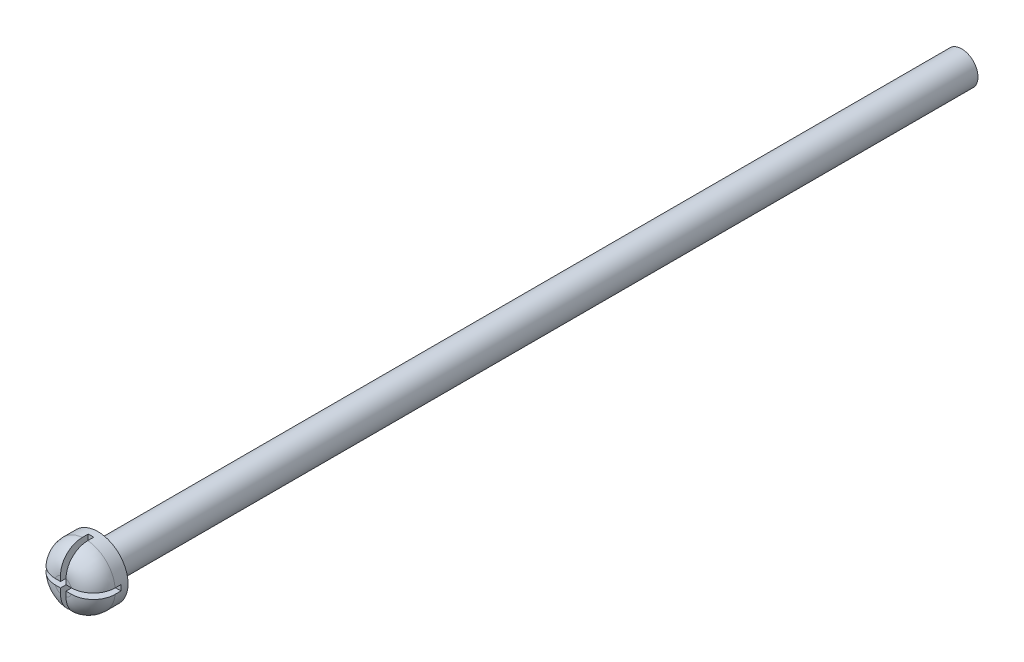
SolidWorks part; units mm, degrees
material "1060 Alloy"
ref_plane "Front Plane" through (0, 0, 0) normal (0, 0, 1) x (1, 0, 0)
ref_plane "Top Plane" through (0, 0, 0) normal (0, 1, 0) x (1, 0, 0)
ref_plane "Right Plane" through (0, 0, 0) normal (1, 0, 0) x (0, 0, -1)
sketch "Sketch1" plane through (0, 0, 0) normal (0, 0, 1) x (1, 0, 0)
  circle A0 centre (0, 0) radius 1.5
  dimension "D1" = 3
extrude "Boss-Extrude1" add sketch "Sketch1" along normal blind 82.55
sketch "Sketch3" plane through (0, 0, 82.55) normal (0, 0, 1) x (1, 0, 0)
  circle A0 centre (0, 0) radius 2.775
  dimension "D1" = 5.55
extrude "Boss-Extrude3" add sketch "Sketch3" against normal blind 3.175
sketch "Sketch4" plane through (0, 0, 82.55) normal (0, 0, 1) x (1, 0, 0)
  line L0 (0, 3.0043) -> (0, -3.0043)
  line L1 (-3.0043, 0) -> (3.0043, 0)
  circle A0 centre (0, 0) radius 3.0043 construction
extrude "Cut-Extrude-Thin1" cut sketch "Sketch4" against normal blind 2.54 thin thin type mid plane wall 0.508
fillet "Fillet2" radius 2 4 edges at (1.9622, -1.9622, 82.55) (1.9622, 1.9622, 82.55) (-1.9622, -1.9622, 82.55) (-1.9622, 1.9622, 82.55)
